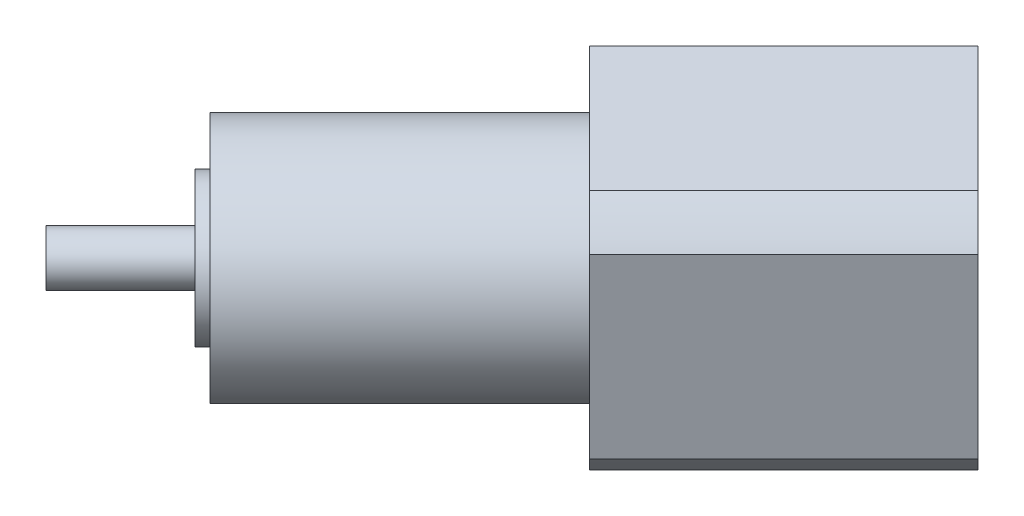
SolidWorks part; units mm, degrees
ref_plane "Plan de face" through (0, 0, 0) normal (0, 0, 1) x (1, 0, 0)
ref_plane "Plan de dessus" through (0, 0, 0) normal (0, 1, 0) x (1, 0, 0)
ref_plane "Plan de droite" through (0, 0, 0) normal (1, 0, 0) x (0, 0, -1)
ref_plane "Plan1" through (79.448, 0, -79.4479) normal (0.7071, 0, -0.7071) x (0, 1, 0)
sketch "Esquisse1" plane through (79.448, 0, -79.4479) normal (0.7071, 0, -0.7071) x (0, 1, 0)
  line L0 (188.7634, 171.0566) -> (157.8366, 171.0566)
  line L1 (152.15, 165.3701) -> (152.15, 134.4432)
  line L2 (157.8366, 128.7566) -> (188.7634, 128.7566)
  line L3 (194.45, 134.4432) -> (194.45, 165.3701)
  arc A0 (157.8366, 171.0566) -> (152.15, 165.3701) centre (173.3, 149.9066) ccw
  arc A1 (152.15, 134.4432) -> (157.8366, 128.7566) centre (173.3, 149.9066) ccw
  arc A2 (188.7634, 128.7566) -> (194.45, 134.4432) centre (173.3, 149.9066) ccw
  arc A3 (194.45, 165.3701) -> (188.7634, 171.0566) centre (173.3, 149.9066) ccw
extrude "Boss.-Extru.1" add sketch "Esquisse1" against normal blind 48
ref_plane "Plan2" through (0, 173.3, 0) normal (0, 1, 0) x (1, 0, 0)
sketch "Esquisse2" plane through (0, 173.3, 0) normal (0, 1, 0) x (1, 0, 0)
  line L0 (164.2135, -73.1999) -> (151.5068, -60.4932)
  line L1 (151.5068, -60.4932) -> (103.9892, -108.0108)
  line L2 (103.9892, -108.0108) -> (106.8177, -110.8392)
  line L3 (106.8177, -110.8392) -> (119.8284, -97.8284)
  line L4 (119.8284, -97.8284) -> (124.7782, -102.7782)
  line L5 (124.7782, -102.7782) -> (126.1217, -101.4347)
  line L6 (126.1217, -101.4347) -> (131.0502, -106.3632)
  line L7 (131.0502, -106.3632) -> (164.2135, -73.1999)
  line L8 (132.6872, -79.3128) -> (127.748, -84.252) construction
revolve "Révolution1" add sketch "Esquisse2" angle 360 about L8
hole_wizard "Diamètre du perçage Ø3.0 (3)1" positions "Esquisse4" profile "Esquisse3" hole size "Ø3.0" standard "Ansi Metric"
sketch "Esquisse4" plane through (45.5069, 0, -45.5068) normal (-0.7071, 0, 0.7071) x (0.7071, 0, 0.7071)
  point P0 (134.4066, 188.8)
  point P1 (134.4066, 157.8)
  point P2 (165.4066, 188.8)
  point P3 (165.4066, 157.8)
sketch "Esquisse3" plane through (140.5467, 188.8, 49.533) normal (0, 1, 0) x (0.7071, 0, 0.7071)
  line L0 (0, 0) -> (0, 10)
  line L1 (0, 10) -> (1.5, 10)
  line L2 (1.5, 10) -> (1.5, 0)
  line L5 (1.5, 0) -> (0, 0)
  line L10 (0, 10) -> (-1.5, 10) construction
  line L11 (0, -6.35) -> (0, 107.95) construction
  dimension "Diamètre du perçage" = 3
  dimension "Profondeur du perçage" = 10
  dimension "Angle de pointe" = 180
hole_wizard "Diamètre du perçage Ø2.0 (2)1" positions "Esquisse6" profile "Esquisse5" hole size "Ø2.0" standard "Ansi Metric"
sketch "Esquisse6" plane through (12.3435, 0, -12.3435) normal (-0.7071, 0, 0.7071) x (0.7071, 0, 0.7071)
  point P0 (149.9066, 159.2)
  point P1 (164.0066, 173.3)
  point P2 (135.8066, 173.3)
  point P3 (149.9066, 187.4)
sketch "Esquisse5" plane through (118.3435, 159.2, 93.6565) normal (0, 1, 0) x (0.7071, 0, 0.7071)
  line L0 (0, 0) -> (0, 9)
  line L1 (0, 9) -> (1, 9)
  line L2 (1, 9) -> (1, 0)
  line L5 (1, 0) -> (0, 0)
  line L10 (0, 9) -> (-1, 9) construction
  line L11 (0, -6.35) -> (0, 107.95) construction
  dimension "Diamètre du perçage" = 2
  dimension "Profondeur du perçage" = 9
  dimension "Angle de pointe" = 180
hole_wizard "Diamètre du perçage Ø3.0 (3)2" positions "Esquisse8" profile "Esquisse7" hole size "Ø3.0" standard "Ansi Metric"
sketch "Esquisse8" plane through (12.3435, 0, -12.3435) normal (-0.7071, 0, 0.7071) x (0.7071, 0, 0.7071)
  point P0 (139.9066, 163.3)
  point P1 (139.9066, 183.3)
  point P2 (159.9066, 183.3)
  point P3 (159.9066, 163.3)
sketch "Esquisse7" plane through (111.2724, 163.3, 86.5854) normal (0, 1, 0) x (0.7071, 0, 0.7071)
  line L0 (0, 0) -> (0, 9)
  line L1 (0, 9) -> (1.5, 9)
  line L2 (1.5, 9) -> (1.5, 0)
  line L5 (1.5, 0) -> (0, 0)
  line L10 (0, 9) -> (-1.5, 9) construction
  line L11 (0, -6.35) -> (0, 107.95) construction
  dimension "Diamètre du perçage" = 3
  dimension "Profondeur du perçage" = 9
  dimension "Angle de pointe" = 180
